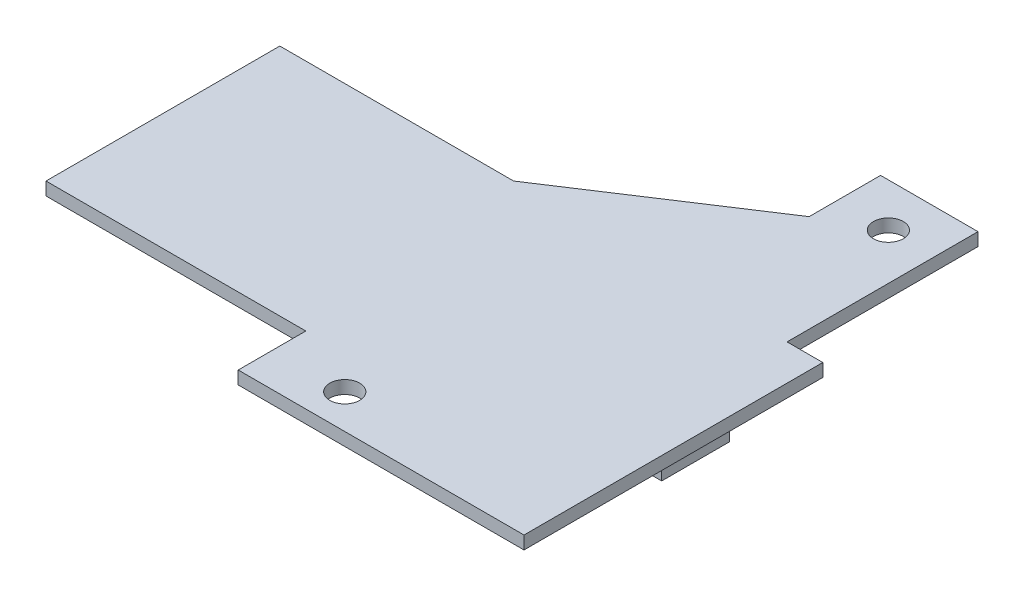
SolidWorks part; units mm, degrees
ref_plane "Спереди" through (0, 0, 0) normal (0, 0, 1) x (1, 0, 0)
ref_plane "Сверху" through (0, 0, 0) normal (0, 1, 0) x (1, 0, 0)
ref_plane "Справа" through (0, 0, 0) normal (1, 0, 0) x (0, 0, -1)
sketch "Эскиз1" plane through (0, 0, 0) normal (0, 1, 0) x (1, 0, 0)
  line L0 (0, 0) -> (-24058.8431, 0) construction
  line L1 (0, 0) -> (0, 24058.8431) construction
  line L13 (0, 0) -> (0, 18)
  line L14 (0, 18) -> (18, 18)
  line L15 (18, 18) -> (31.75, 27)
  line L16 (31.75, 27) -> (31.75, 32.5)
  line L17 (31.75, 32.5) -> (39.25, 32.5)
  line L18 (39.25, 32.5) -> (39.25, 17.8)
  line L19 (39.25, 17.8) -> (42, 17.8)
  line L20 (42, 17.8) -> (42, -5.2)
  line L21 (42, -5.2) -> (20, -5.2)
  line L22 (20, -5.2) -> (20, 0)
  line L23 (20, 0) -> (0, 0)
  dimension "D1" = 18
  dimension "D2" = 18
  dimension "D3" = 42
  dimension "D4" = 7.5
  dimension "D5" = 5.5
  dimension "D6" = 14.7
  dimension "D7" = 2.75
  dimension "D8" = 23
  dimension "D9" = 14.5
  dimension "D10" = 22
  dimension "D11" = 37.7
extrude "Бобышка-Вытянуть1" add sketch "Эскиз1" along normal blind 1
sketch "Эскиз2" plane through (0, 1, 0) normal (0, 1, 0) x (1, 0, 0)
  line L0 (39.25, 17.8) -> (39.25, 32.5) construction
  line L2 (31.75, 32.5) -> (31.75, 27) construction
  line L5 (39.25, 32.5) -> (31.75, 32.5) construction
  circle A0 centre (35.7, 29.15) radius 1.15
  dimension "D1" = 2.3
  dimension "D3" = 2.8
  dimension "D4" = 2.2
  dimension "D2" = 2.4
extrude "Вырез-Вытянуть1" cut sketch "Эскиз2" against normal through all
sketch "Эскиз3" plane through (0, 1, 0) normal (0, 1, 0) x (1, 0, 0)
  line L1 (20, -5.2) -> (42, -5.2) construction
  line L6 (20, 0) -> (20, -5.2) construction
  line L10 (42, -5.2) -> (42, 17.8) construction
  circle A0 centre (25.55, -2.55) radius 1.15
  dimension "D1" = 2.3
  dimension "D2" = 1.5
  dimension "D3" = 4.4
  dimension "D4" = 15.3
extrude "Вырез-Вытянуть2" cut sketch "Эскиз3" against normal through all
sketch "Эскиз4" plane through (0, 0, 0) normal (0, -1, 0) x (1, 0, 0)
  line L0 (0, -18) -> (0, 0) construction
  line L1 (41, -11.6) -> (35.8, -11.6)
  line L2 (41, -11.6) -> (41, -6.4)
  line L3 (41, -6.4) -> (35.8, -6.4)
  line L4 (35.8, -11.6) -> (35.8, -6.4)
  line L5 (41, -11.6) -> (35.8, -6.4) construction
  line L6 (41, -6.4) -> (35.8, -11.6) construction
  line L7 (20, 5.2) -> (42, 5.2) construction
  point P0 (38.4, -9)
  dimension "D1" = 5.2
  dimension "D2" = 41
  dimension "D3" = 16.8
extrude "Бобышка-Вытянуть2" add sketch "Эскиз4" along normal blind 1.7
